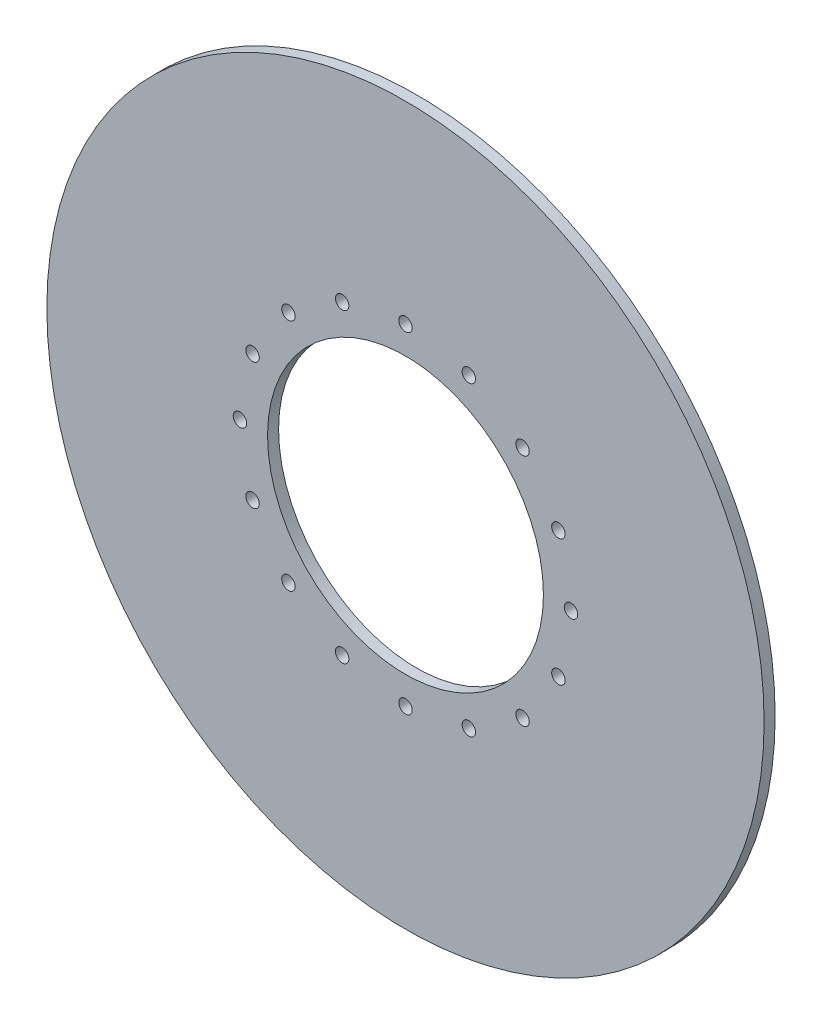
SolidWorks part; units mm, degrees
material "AISI 304"
ref_plane "Front Plane" through (0, 0, 0) normal (0, 0, 1) x (1, 0, 0)
ref_plane "Top Plane" through (0, 0, 0) normal (0, 1, 0) x (1, 0, 0)
ref_plane "Right Plane" through (0, 0, 0) normal (1, 0, 0) x (0, 0, -1)
sketch "Sketch1" plane through (0, 0, 0) normal (0, 0, 1) x (1, 0, 0)
  line L0 (0, 0) -> (0, 441.7053) construction
  line L3 (0, 0) -> (185.4371, 447.6848) construction
  line L4 (46.943, 191.8401) -> (71.3058, 291.4026) construction
  line L9 (226.8514, -146.4443) -> (147.5642, -85.5018) construction
  line L10 (85.3562, -147.7098) -> (146.2341, -227.0473) construction
  line L11 (56.8537, -258.9599) -> (43.882, -159.8025) construction
  line L12 (-44.0933, -159.8025) -> (-57.1463, -258.9498) construction
  line L13 (-146.4443, -226.8514) -> (-85.5018, -147.5642) construction
  line L14 (-147.7098, -85.3562) -> (-227.0473, -146.2341) construction
  line L18 (102.4577, 168.8451) -> (155.632, 256.4736) construction
  line L19 (191.8401, 46.943) -> (291.4026, 71.3058) construction
  line L20 (168.8451, 102.4577) -> (256.4736, 155.632) construction
  line L21 (168.8451, -102.4577) -> (256.4736, -155.632) construction
  line L22 (191.8401, -46.943) -> (291.4026, -71.3058) construction
  line L23 (46.943, -191.8401) -> (71.3058, -291.4026) construction
  line L24 (102.4577, -168.8451) -> (155.632, -256.4736) construction
  line L25 (-102.4577, -168.8451) -> (-155.632, -256.4736) construction
  line L26 (-46.943, -191.8401) -> (-71.3058, -291.4026) construction
  line L27 (-191.8401, -46.943) -> (-291.4026, -71.3058) construction
  line L28 (-168.8451, -102.4577) -> (-256.4736, -155.632) construction
  line L29 (-168.8451, 102.4577) -> (-256.4736, 155.632) construction
  line L30 (-191.8401, 46.943) -> (-291.4026, 71.3058) construction
  line L31 (-46.943, 191.8401) -> (-71.3058, 291.4026) construction
  line L32 (-102.4577, 168.8451) -> (-155.632, 256.4736) construction
  circle A1 centre (0, 0) radius 325
  circle A2 centre (0, 0) radius 125
  circle A5 centre (0, 0) radius 197.5 construction
  circle A6 centre (0, 0) radius 300 construction
  arc A11 (146.2341, -227.0473) -> (226.8514, -146.4443) centre (-136.1908, 136.0452) ccw construction
  arc A12 (85.3562, -147.7098) -> (147.5642, -85.5018) centre (-136.1908, 136.0452) ccw construction
  arc A13 (-57.1463, -258.9498) -> (56.8537, -258.9599) centre (-0.1056, 197.5) ccw construction
  arc A14 (-44.0933, -159.8025) -> (43.882, -159.8025) centre (-0.1056, 197.5) ccw construction
  arc A15 (-227.0473, -146.2341) -> (-146.4443, -226.8514) centre (136.0452, 136.1908) ccw construction
  arc A16 (-147.7098, -85.3562) -> (-85.5018, -147.5642) centre (136.0452, 136.1908) ccw construction
  arc A20 (46.943, 191.8401) -> (102.4577, 168.8451) centre (0, 0) cw construction
  arc A21 (71.3058, 291.4026) -> (155.632, 256.4736) centre (0, 0) cw construction
  arc A22 (256.4736, 155.632) -> (291.4026, 71.3058) centre (0, 0) cw construction
  arc A23 (168.8451, 102.4577) -> (191.8401, 46.943) centre (0, 0) cw construction
  arc A24 (291.4026, -71.3058) -> (256.4736, -155.632) centre (0, 0) cw construction
  arc A25 (191.8401, -46.943) -> (168.8451, -102.4577) centre (0, 0) cw construction
  arc A26 (155.632, -256.4736) -> (71.3058, -291.4026) centre (0, 0) cw construction
  arc A27 (102.4577, -168.8451) -> (46.943, -191.8401) centre (0, 0) cw construction
  arc A28 (-71.3058, -291.4026) -> (-155.632, -256.4736) centre (0, 0) cw construction
  arc A29 (-46.943, -191.8401) -> (-102.4577, -168.8451) centre (0, 0) cw construction
  arc A30 (-256.4736, -155.632) -> (-291.4026, -71.3058) centre (0, 0) cw construction
  arc A31 (-168.8451, -102.4577) -> (-191.8401, -46.943) centre (0, 0) cw construction
  arc A32 (-291.4026, 71.3058) -> (-256.4736, 155.632) centre (0, 0) cw construction
  arc A33 (-191.8401, 46.943) -> (-168.8451, 102.4577) centre (0, 0) cw construction
  arc A34 (-155.632, 256.4736) -> (-71.3058, 291.4026) centre (0, 0) cw construction
  arc A35 (-102.4577, 168.8451) -> (-46.943, 191.8401) centre (0, 0) cw construction
  circle A36 centre (0, 150) radius 6.1
  circle A37 centre (57.4025, 138.5819) radius 6.1
  circle A38 centre (106.066, 106.066) radius 6.1
  circle A39 centre (138.5819, 57.4025) radius 6.1
  circle A40 centre (150, 0) radius 6.1
  circle A41 centre (138.5819, -57.4025) radius 6.1
  circle A42 centre (106.066, -106.066) radius 6.1
  circle A43 centre (57.4025, -138.5819) radius 6.1
  circle A44 centre (0, -150) radius 6.1
  circle A45 centre (-57.4025, -138.5819) radius 6.1
  circle A46 centre (-106.066, -106.066) radius 6.1
  circle A47 centre (-138.5819, -57.4025) radius 6.1
  circle A48 centre (-150, 0) radius 6.1
  circle A49 centre (-138.5819, 57.4025) radius 6.1
  circle A50 centre (-106.066, 106.066) radius 6.1
  circle A51 centre (-57.4025, 138.5819) radius 6.1
  circle A52 centre (0, 0) radius 150 construction
  point P54 (0, 0)
  point P70 (0, 0)
  point P95 (0, 0)
  dimension "D1" = 250
  dimension "D2" = 650
  dimension "D5" = 395
  dimension "D3" = 600
  dimension "D6" = 17.5
  dimension "D7" = 8
  dimension "D8" = 12.2
  dimension "D11" = 300
  dimension "D4" = 22.5
  dimension "D9" = 150
  dimension "D10" = 16
extrude "Boss-Extrude1" add sketch "Sketch1" along normal blind 10
